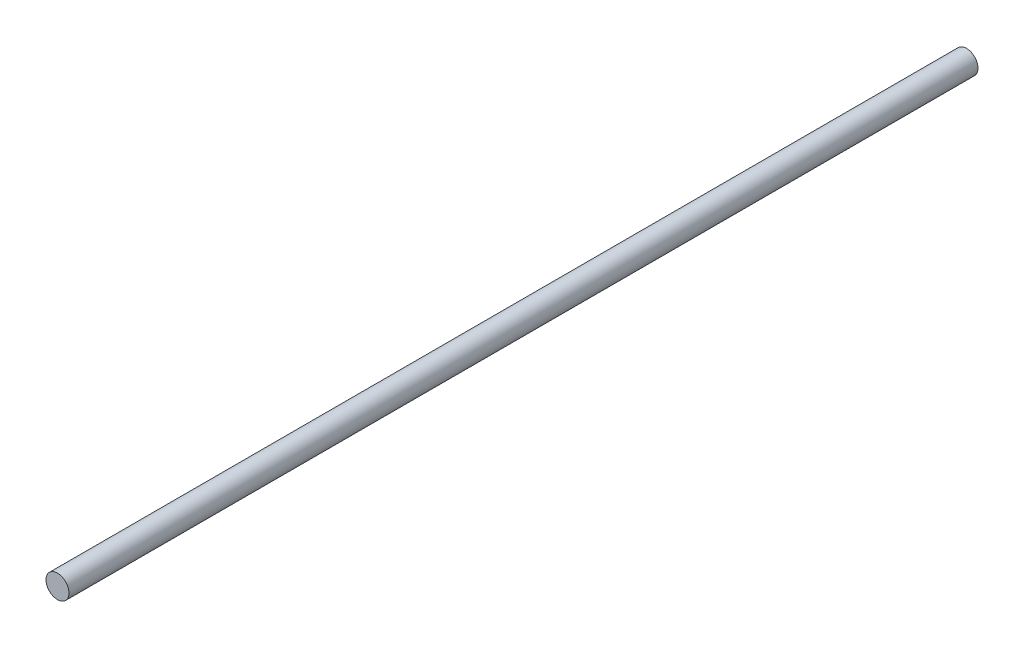
SolidWorks part; units mm, degrees
material "1023 Carbon Steel Sheet (SS)"
ref_plane "Front Plane" through (0, 0, 0) normal (1, 0, 0) x (0, 1, 0)
ref_plane "Top Plane" through (0, 0, 0) normal (0, 0, 1) x (0, 1, 0)
ref_plane "Right Plane" through (0, 0, 0) normal (0, 1, 0) x (-1, 0, 0)
sketch "Sketch1" plane through (0, 0, 0) normal (0, 0, 1) x (0, 1, 0)
  circle A0 centre (0, 0) radius 4
  dimension "D1" = 8
extrude "Boss-Extrude1" add sketch "Sketch1" along normal blind 316 contours A0
